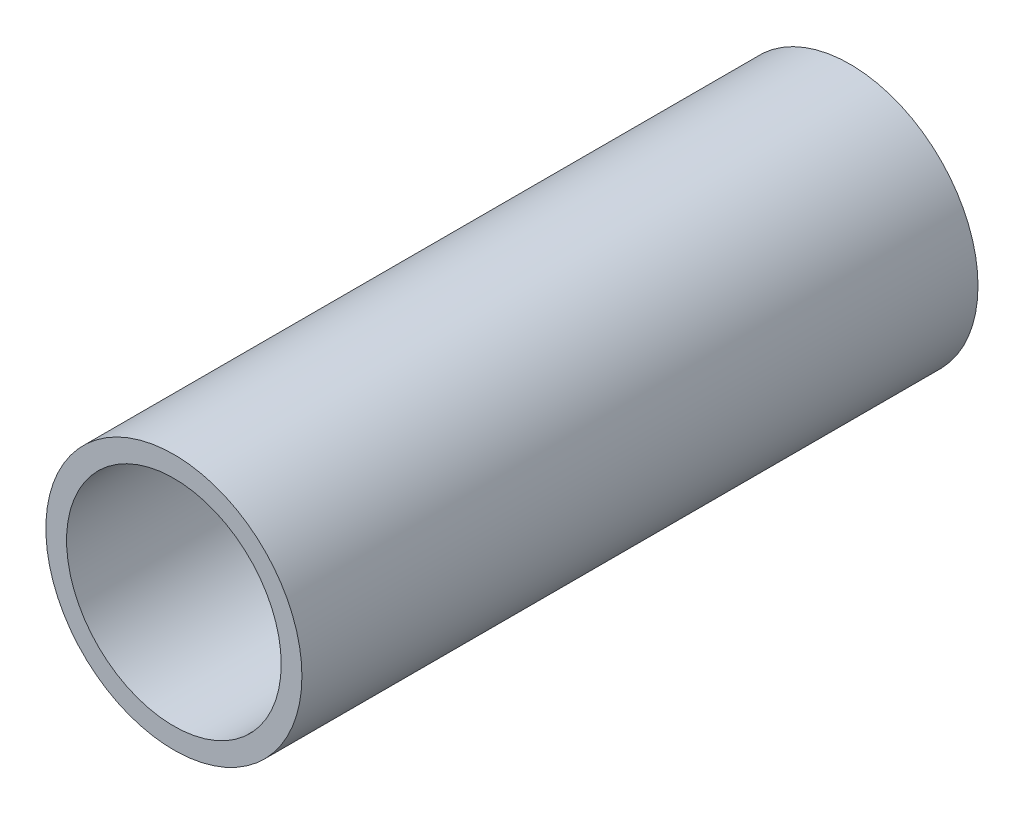
SolidWorks part; units mm, degrees
ref_plane "Front Plane" through (0, 0, 0) normal (0, 0, 1) x (1, 0, 0)
ref_plane "Top Plane" through (0, 0, 0) normal (0, 1, 0) x (1, 0, 0)
ref_plane "Right Plane" through (0, 0, 0) normal (1, 0, 0) x (0, 0, -1)
sketch "Sketch1" plane through (0, 0, 0) normal (0, 0, 1) x (1, 0, 0)
  circle A0 centre (0, 0) radius 30.3
  circle A1 centre (0, 0) radius 25.4
  dimension "D1" = 60.6
  dimension "D2" = 50.8
extrude "Boss-Extrude1" add sketch "Sketch1" along normal blind 160
